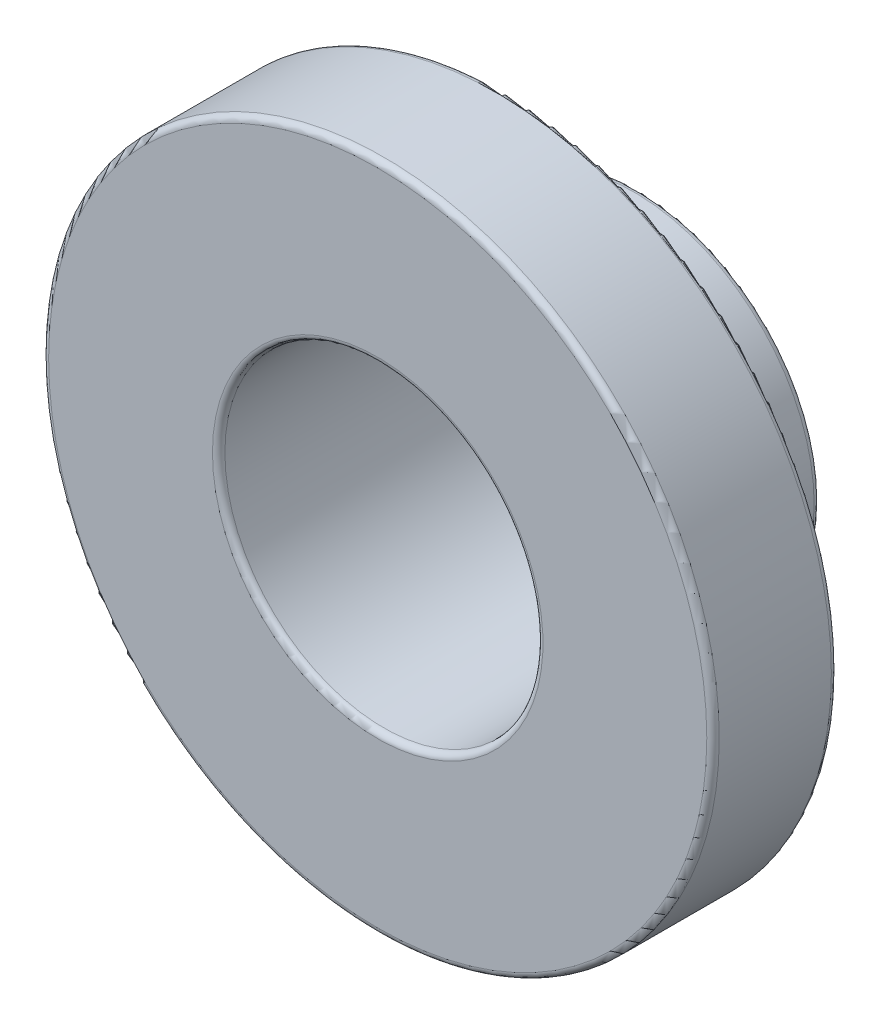
SolidWorks part; units mm, degrees
ref_plane "Front Plane" through (0, 0, 0) normal (0, 0, 1) x (1, 0, 0)
ref_plane "Top Plane" through (0, 0, 0) normal (0, 1, 0) x (1, 0, 0)
ref_plane "Right Plane" through (0, 0, 0) normal (1, 0, 0) x (0, 0, -1)
sketch "Sketch1" plane through (0, 0, 0) normal (-1, 0, 0) x (0, 0, 1)
  line L0 (1.2573, 1.524) -> (-1.2573, 1.524)
  line L1 (-1.2573, 1.524) -> (-1.2573, 1.7272)
  line L2 (-1.2573, 1.7272) -> (0.0635, 1.7272)
  line L3 (0.0635, 1.7272) -> (0.0635, 3.2131)
  line L4 (0.0635, 3.2131) -> (1.2573, 3.2131)
  line L6 (1.2573, 3.2131) -> (1.2573, 1.524)
  line L7 (1.2573, 0) -> (-1.2573, 0) construction
  dimension "ID" = 3.048
  dimension "OD" = 6.4262
  dimension "Sleeve OD" = 3.4544
  dimension "Thickness" = 1.1938
  dimension "Overall Height" = 2.5146
sketch "Sketch2" plane through (0, 0, 0) normal (1, 0, 0) x (0, 0, -1)
  line L6 (-1.2573, 1.524) -> (1.2573, 1.524)
  line L7 (1.2573, 1.524) -> (1.2573, 1.7272)
  line L8 (1.2573, 1.7272) -> (-0.0635, 1.7272)
  line L9 (-0.0635, 1.7272) -> (-0.0635, 3.2131)
  line L10 (-0.0635, 3.2131) -> (-1.2573, 3.2131)
  line L11 (-1.2573, 3.2131) -> (-1.2573, 1.524)
  line L12 (-1.2573, 1.524) -> (1.2573, 1.524)
  line L13 (1.2573, 1.524) -> (1.2573, 1.7272)
  line L14 (1.2573, 1.7272) -> (-0.0635, 1.7272)
  line L15 (-0.0635, 1.7272) -> (-0.0635, 3.2131)
  line L16 (-0.0635, 3.2131) -> (-1.2573, 3.2131)
  line L17 (-1.2573, 3.2131) -> (-1.2573, 1.524)
  dimension "D1" = 0
revolve "Revolve1" add sketch "Sketch2" angle 360 about L7
fillet "Fillet1" radius 0.0597 6 edges at (1.524, 0, 1.2573) (1.524, 0, -1.2573) (1.7272, 0, -1.2573) (1.7272, 0, 0.0635) (3.2131, 0, 0.0635) (3.2131, 0, 1.2573)
equation "\"D1@Fillet1\"=\"Thickness@Sketch1\"*0.05"
